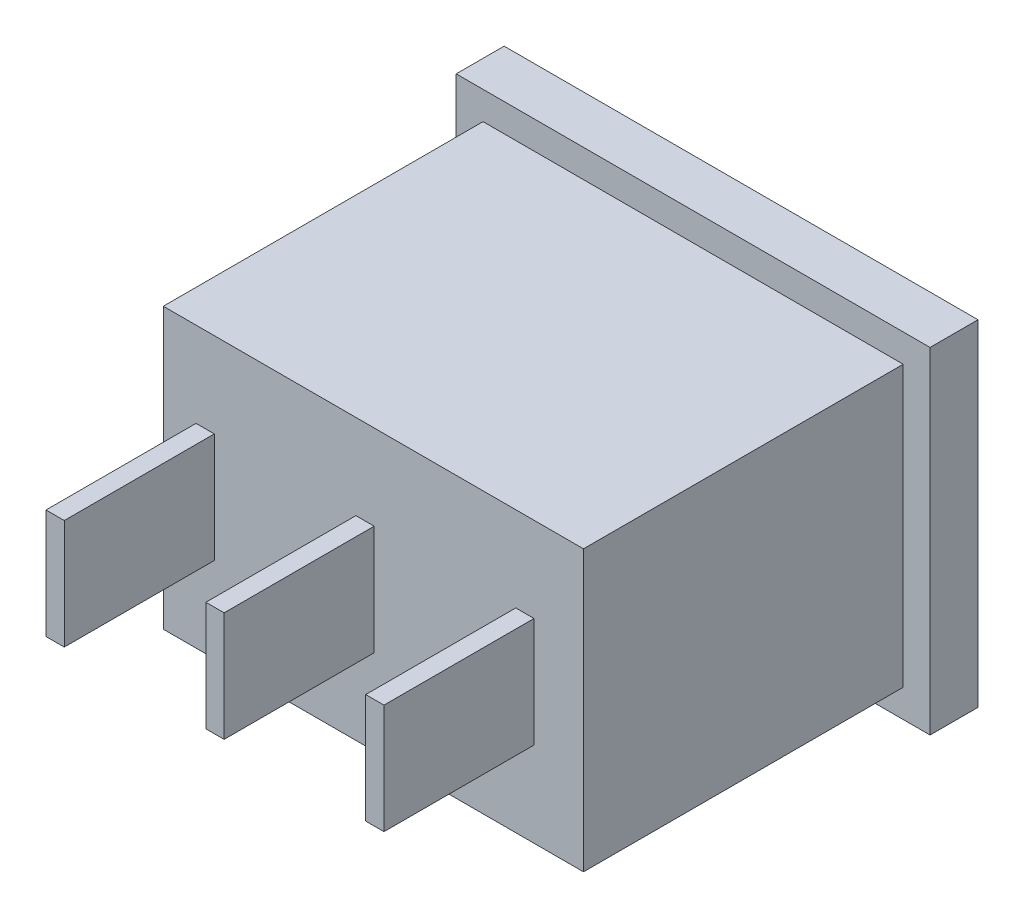
SolidWorks part; units mm, degrees
ref_plane "Plan de face" through (0, 0, 0) normal (0, 0, 1) x (1, 0, 0)
ref_plane "Plan de dessus" through (0, 0, 0) normal (0, 1, 0) x (1, 0, 0)
ref_plane "Plan de droite" through (0, 0, 0) normal (1, 0, 0) x (0, 0, -1)
sketch "Esquisse1" plane through (0, 0, 0) normal (0, 0, 1) x (1, 0, 0)
  line L1 (-10.375, 7.35) -> (10.375, 7.35)
  line L2 (-10.375, 7.35) -> (-10.375, -7.35)
  line L3 (-10.375, -7.35) -> (10.375, -7.35)
  line L4 (10.375, 7.35) -> (10.375, -7.35)
  point P4 (-10.375, 0)
  point P6 (0, 7.35)
  dimension "D1" = 20.75
  dimension "D2" = 14.7
extrude "Boss.-Extru.1" add sketch "Esquisse1" along normal blind 2.1
sketch "Esquisse2" plane through (0, 0, 2.1) normal (0, 0, 1) x (1, 0, 0)
  line L0 (10.375, 7.35) -> (-10.375, 7.35) construction
  line L1 (-9.2, 6.125) -> (9.2, 6.125)
  line L2 (-9.2, 6.125) -> (-9.2, -6.125)
  line L3 (-9.2, -6.125) -> (9.2, -6.125)
  line L4 (9.2, 6.125) -> (9.2, -6.125)
  line L5 (10.375, -7.35) -> (10.375, 7.35) construction
  point P6 (0, 7.35)
  point P7 (0, 6.125)
  point P10 (10.375, 0)
  point P11 (9.2, 0)
  dimension "D1" = 18.4
  dimension "D2" = 12.25
extrude "Boss.-Extru.2" add sketch "Esquisse2" along normal blind 14
sketch "Esquisse3" plane through (0, 0, 16.1) normal (0, 0, 1) x (1, 0, 0)
  line L0 (-9.2, 6.125) -> (-9.2, -6.125) construction
  line L1 (-0.7666, 2.4) -> (0.0334, 2.4)
  line L2 (-0.7666, 2.4) -> (-0.7666, -2.4)
  line L3 (-0.7666, -2.4) -> (0.0334, -2.4)
  line L4 (0.0334, 2.4) -> (0.0334, -2.4)
  line L5 (6.2334, 2.4) -> (7.0334, 2.4)
  line L6 (6.2334, 2.4) -> (6.2334, -2.4)
  line L7 (6.2334, -2.4) -> (7.0334, -2.4)
  line L8 (7.0334, 2.4) -> (7.0334, -2.4)
  line L9 (-7.7666, 2.4) -> (-6.9666, 2.4)
  line L10 (-7.7666, 2.4) -> (-7.7666, -2.4)
  line L11 (-7.7666, -2.4) -> (-6.9666, -2.4)
  line L12 (-6.9666, 2.4) -> (-6.9666, -2.4)
  line L13 (-7.3666, -2.4) -> (-0.3666, -2.4) construction
  line L14 (-0.3666, -2.4) -> (6.6334, -2.4) construction
  point P12 (-7.7666, 0)
  point P15 (-9.2, 0)
  dimension "D1" = 0.8
  dimension "D2" = 4.8
  dimension "D3" = 7
extrude "Boss.-Extru.3" add sketch "Esquisse3" along normal blind 6.57
sketch "Esquisse4" plane through (0, 0, 0) normal (0, 0, -1) x (-1, 0, 0)
  line L0 (10.375, 7.35) -> (10.375, -7.35) construction
  line L1 (7.495, -4.75) -> (-7.495, -4.75)
  line L2 (7.495, -4.75) -> (7.495, 4.75)
  line L3 (7.495, 4.75) -> (-7.495, 4.75)
  line L4 (-7.495, -4.75) -> (-7.495, 4.75)
  line L5 (-10.375, 7.35) -> (10.375, 7.35) construction
  point P4 (7.495, 0)
  point P7 (10.375, 0)
  point P8 (0, 4.75)
  point P11 (0, 7.35)
  dimension "D1" = 14.99
  dimension "D2" = 9.5
extrude "Boss.-Extru.4" add sketch "Esquisse4" along normal blind 2
sketch "Esquisse5" plane through (0, 4.75, 0) normal (0, 1, 0) x (1, 0, 0)
  line L0 (-7.495, 2) -> (7.495, 2) construction
  line L1 (-7.495, 0) -> (7.495, 0) construction
  line L2 (-7.495, 2) -> (7.495, 2)
  arc A0 (-7.495, 2) -> (7.495, 2) centre (0, 26) ccw
  point P9 (0, 2)
  dimension "D1" = 26
extrude "Enlèv. mat.-Extru.1" cut sketch "Esquisse5" against normal up to next
